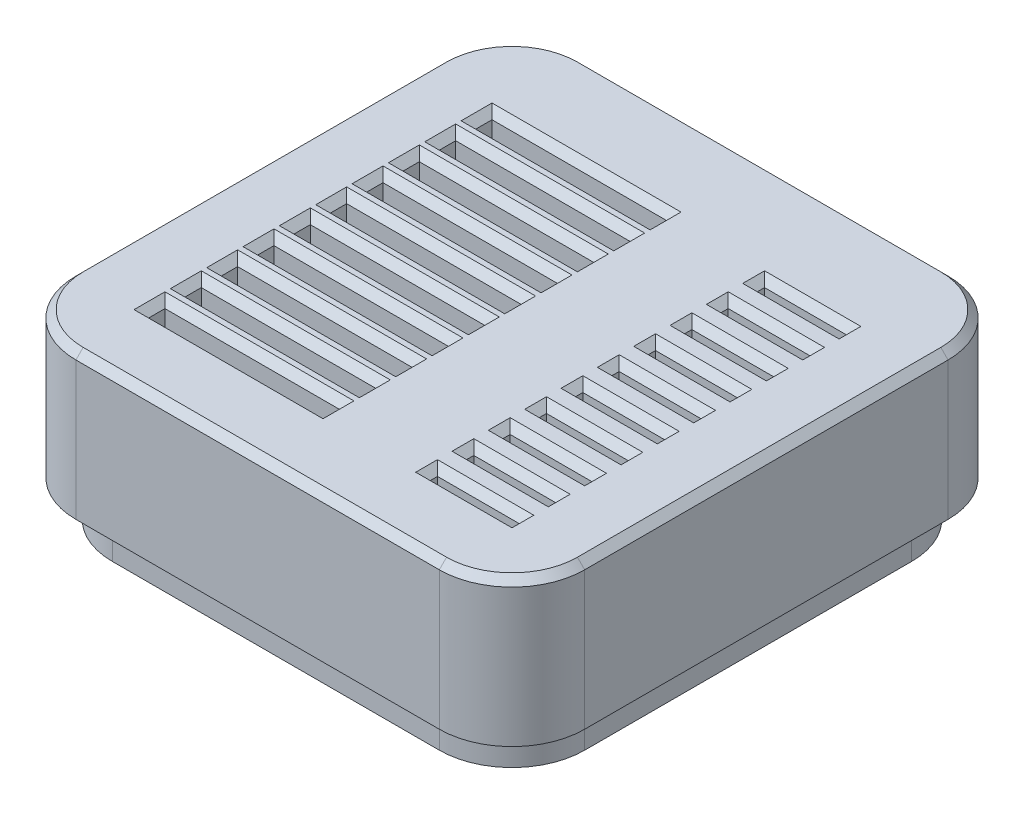
SolidWorks part; units mm, degrees
ref_plane "Front Plane" through (0, 0, 0) normal (0, 0, 1) x (1, 0, 0)
ref_plane "Top Plane" through (0, 0, 0) normal (0, 1, 0) x (1, 0, 0)
ref_plane "Right Plane" through (0, 0, 0) normal (1, 0, 0) x (0, 0, -1)
sketch "Sketch5" plane through (0, 0, 0) normal (0, 1, 0) x (1, 0, 0)
  line L1 (-22.5, -32.5) -> (22.5, -32.5)
  line L2 (-32.5, -22.5) -> (-32.5, 22.5)
  line L3 (-22.5, 32.5) -> (22.5, 32.5)
  line L4 (32.5, -22.5) -> (32.5, 22.5)
  line L5 (-32.5, -32.5) -> (32.5, 32.5) construction
  line L6 (-32.5, 32.5) -> (32.5, -32.5) construction
  arc A0 (-22.5, -32.5) -> (-32.5, -22.5) centre (-22.5, -22.5) cw
  arc A1 (22.5, -32.5) -> (32.5, -22.5) centre (22.5, -22.5) ccw
  arc A2 (22.5, 32.5) -> (32.5, 22.5) centre (22.5, 22.5) cw
  arc A3 (-32.5, 22.5) -> (-22.5, 32.5) centre (-22.5, 22.5) cw
  point P0 (0, 0)
  dimension "D3" = 10
  dimension "D1" = 65
  dimension "D2" = 65
extrude "Boss-Extrude4" add sketch "Sketch5" along normal blind 5
sketch "Sketch6" plane through (0, 5, 0) normal (0, 1, 0) x (1, 0, 0)
  line L1 (35, 35) -> (-35, 35)
  line L2 (35, 35) -> (35, -35)
  line L3 (35, -35) -> (-35, -35)
  line L4 (-35, 35) -> (-35, -35)
  line L5 (35, 35) -> (-35, -35) construction
  line L6 (35, -35) -> (-35, 35) construction
  point P0 (0, 0)
extrude "Boss-Extrude5" add sketch "Sketch6" along normal blind 20
sketch "Sketch8" plane through (0, 0, 0) normal (0, -1, 0) x (1, 0, 0)
  line L0 (-29.5711, 29.5711) -> (-22.5, 22.5)
  arc A0 (-22.5, 32.5) -> (-32.5, 22.5) centre (-22.5, 22.5) ccw construction
  circle A1 centre (-26.0355, 26.0355) radius 3
  circle A2 centre (26.0365, 26.0365) radius 3
  circle A3 centre (26.0375, -26.0355) radius 3
  circle A4 centre (-26.0345, -26.0365) radius 3
  point P8 (0, 0)
  point P15 (0.001, 0.001)
  point P18 (0.002, 0)
  point P21 (0.001, -0.001)
  point P22 (0.001, 0)
  dimension "D1" = 4
extrude "Cut-Extrude1" cut sketch "Sketch8" against normal blind 2 contours A3 | A2 | L0 A1 | L0 A1 | A4
fillet "Fillet1" radius 10 4 edges at (-35, 15, -35) (-35, 15, 35) (35, 15, 35) (35, 15, -35)
sketch "Sketch9" plane through (0, 25, 0) normal (0, 1, 0) x (1, 0, 0)
  line L0 (-35, 25) -> (35, 25)
  line L1 (-25, -20) -> (-25, -17.75)
  line L2 (25, 35) -> (25, -35)
  line L3 (-25, -25) -> (-1, -25)
  line L4 (35, -25) -> (-35, -25)
  line L5 (-25, -25) -> (-25, -22.75)
  line L6 (-25, -35) -> (-25, 35)
  line L7 (-25, -22.75) -> (-1, -22.75)
  line L8 (-1, -25) -> (-1, -22.75)
  line L9 (-25, -20) -> (-1, -20)
  line L10 (-1, -20) -> (-1, -17.75)
  line L11 (-25, -17.75) -> (-1, -17.75)
  line L12 (-25, -15) -> (-25, -12.75)
  line L13 (-25, -15) -> (-1, -15)
  line L14 (-1, -15) -> (-1, -12.75)
  line L15 (-25, -12.75) -> (-1, -12.75)
  line L16 (-25, -10) -> (-25, -7.75)
  line L17 (-25, -10) -> (-1, -10)
  line L18 (-1, -10) -> (-1, -7.75)
  line L19 (-25, -7.75) -> (-1, -7.75)
  line L20 (-25, -5) -> (-25, -2.75)
  line L21 (-25, -5) -> (-1, -5)
  line L22 (-1, -5) -> (-1, -2.75)
  line L23 (-25, -2.75) -> (-1, -2.75)
  line L24 (-25, 0) -> (-25, 2.25)
  line L25 (-25, 0) -> (-1, 0)
  line L26 (-1, 0) -> (-1, 2.25)
  line L27 (-25, 2.25) -> (-1, 2.25)
  line L28 (-25, 5) -> (-25, 7.25)
  line L29 (-25, 5) -> (-1, 5)
  line L30 (-1, 5) -> (-1, 7.25)
  line L31 (-25, 7.25) -> (-1, 7.25)
  line L32 (-25, 10) -> (-25, 12.25)
  line L33 (-25, 10) -> (-1, 10)
  line L34 (-1, 10) -> (-1, 12.25)
  line L35 (-25, 12.25) -> (-1, 12.25)
  line L36 (-25, 15) -> (-25, 17.25)
  line L37 (-25, 15) -> (-1, 15)
  line L38 (-1, 15) -> (-1, 17.25)
  line L39 (-25, 17.25) -> (-1, 17.25)
  line L40 (-25, 20) -> (-25, 22.25)
  line L41 (-25, 20) -> (-1, 20)
  line L42 (-1, 20) -> (-1, 22.25)
  line L43 (-25, 22.25) -> (-1, 22.25)
  arc A0 (25, -35) -> (35, -25) centre (25, -25) ccw construction
  point P4 (-25, -25)
  point P20 (25, -25)
  point P21 (25, 25)
  point P22 (-25, 25)
  dimension "D1" = 24
  dimension "D2" = 2.25
  dimension "D3" = 10
extrude "Cut-Extrude2" cut sketch "Sketch9" against normal blind 15 contours L3 L8 L7 L5 | L11 L1 L9 L10 | L15 L6 L13 L14 | L23 L6 L21 L22 | L27 L6 L25 L26 | L31 L6 L29 L30 | L35 L6 L33 L34 | L39 L6 L37 L38 | L43 L6 L41 L42 | L17 L18 L19 L16
sketch "Sketch10" plane through (0, 25, 0) normal (0, 1, 0) x (1, 0, 0)
  line L0 (-25, -35) -> (-25, 35)
  line L1 (25, -20) -> (25, -19)
  line L2 (-35, 25) -> (35, 25)
  line L3 (25, -25) -> (13.75, -25)
  line L4 (25, 35) -> (25, -35)
  line L5 (25, -25) -> (25, -24)
  line L6 (35, -25) -> (-35, -25)
  line L7 (25, -24) -> (13.75, -24)
  line L8 (13.75, -25) -> (13.75, -24)
  line L9 (25, -20) -> (13.75, -20)
  line L10 (13.75, -20) -> (13.75, -19)
  line L11 (25, -19) -> (13.75, -19)
  line L12 (25, -15) -> (25, -14)
  line L13 (25, -15) -> (13.75, -15)
  line L14 (13.75, -15) -> (13.75, -14)
  line L15 (25, -14) -> (13.75, -14)
  line L16 (25, -10) -> (25, -9)
  line L17 (25, -10) -> (13.75, -10)
  line L18 (13.75, -10) -> (13.75, -9)
  line L19 (25, -9) -> (13.75, -9)
  line L20 (25, -5) -> (25, -4)
  line L21 (25, -5) -> (13.75, -5)
  line L22 (13.75, -5) -> (13.75, -4)
  line L23 (25, -4) -> (13.75, -4)
  line L24 (25, 0) -> (25, 1)
  line L25 (25, 0) -> (13.75, 0)
  line L26 (13.75, 0) -> (13.75, 1)
  line L27 (25, 1) -> (13.75, 1)
  line L28 (25, 5) -> (25, 6)
  line L29 (25, 5) -> (13.75, 5)
  line L30 (13.75, 5) -> (13.75, 6)
  line L31 (25, 6) -> (13.75, 6)
  line L32 (25, 10) -> (25, 11)
  line L33 (25, 10) -> (13.75, 10)
  line L34 (13.75, 10) -> (13.75, 11)
  line L35 (25, 11) -> (13.75, 11)
  line L36 (25, 15) -> (25, 16)
  line L37 (25, 15) -> (13.75, 15)
  line L38 (13.75, 15) -> (13.75, 16)
  line L39 (25, 16) -> (13.75, 16)
  line L40 (25, 20) -> (25, 21)
  line L41 (25, 20) -> (13.75, 20)
  line L42 (13.75, 20) -> (13.75, 21)
  line L43 (25, 21) -> (13.75, 21)
  dimension "D1" = 11.25
  dimension "D2" = 1
  dimension "D3" = 10
extrude "Cut-Extrude3" cut sketch "Sketch10" against normal blind 10 contours L8 L3 L4 L7 | L1 L11 L10 L9 | L4 L15 L14 L13 | L4 L19 L18 L17 | L4 L27 L26 L25 | L4 L31 L30 L29 | L4 L35 L34 L33 | L4 L39 L38 L37 | L4 L43 L42 L41 | L23 L22 L21 L20
chamfer "Chamfer1" distance 1 angle 45 87 edges at (19.375, 25, 25) (25, 25, -20.5) (25, 25, -10.5) (25, 25, -0.5) (25, 25, 14.5) (25, 25, 9.5) (25, 25, -5.5) (25, 25, -15.5) (19.375, 25, 24) (13.75, 25, 24.5) (13.75, 25, 4.5) (19.375, 25, 5) (25, 25, 4.5) (19.375, 25, 4) (19.375, 25, -16) (13.75, 25, -15.5) (19.375, 25, -15) (19.375, 25, -6) (13.75, 25, -5.5) (19.375, 25, -5) (19.375, 25, 9) (13.75, 25, 9.5) (19.375, 25, 10) (-13, 25, 10) (-1, 25, 8.875) (-13, 25, 7.75) (-25, 25, 8.875) (-25, 25, -16.125) (-13, 25, -15) (-1, 25, -16.125) (-13, 25, -17.25) (-25, 25, -6.125) (-13, 25, -5) (-1, 25, -6.125) (-13, 25, -7.25) (-25, 25, 3.875) (-13, 25, 5) (-1, 25, 3.875) (-13, 25, 2.75) (-25, 25, 18.875) (-13, 25, 20) (-1, 25, 18.875) (-13, 25, 17.75) (32.0711, 25, -32.0711) (35, 25, 0) (32.0711, 25, 32.0711) (0, 25, 35) (-32.0711, 25, 32.0711) (-35, 25, 0) (-32.0711, 25, -32.0711) (0, 25, -35) (-25, 25, 13.875) (-13, 25, 15) (-1, 25, 13.875) (-13, 25, 12.75) (-25, 25, -1.125) (-13, 25, 0) (-1, 25, -1.125) (-13, 25, -2.25) (-25, 25, -11.125) (-13, 25, -10) (-1, 25, -11.125) (-13, 25, -12.25) (-25, 25, -21.125) (-13, 25, -20) (-1, 25, -21.125) (-13, 25, -22.25) (-13, 25, 22.75) (-25, 25, 23.875) (-13, 25, 25) (-1, 25, 23.875) (13.75, 25, 19.5) (19.375, 25, 20) (25, 25, 19.5) (19.375, 25, 19) (19.375, 25, 14) (13.75, 25, 14.5) (19.375, 25, 15) (19.375, 25, -1) (13.75, 25, -0.5) (19.375, 25, 0) (19.375, 25, -11) (13.75, 25, -10.5) (19.375, 25, -10) (19.375, 25, -21) (13.75, 25, -20.5) (19.375, 25, -20)
